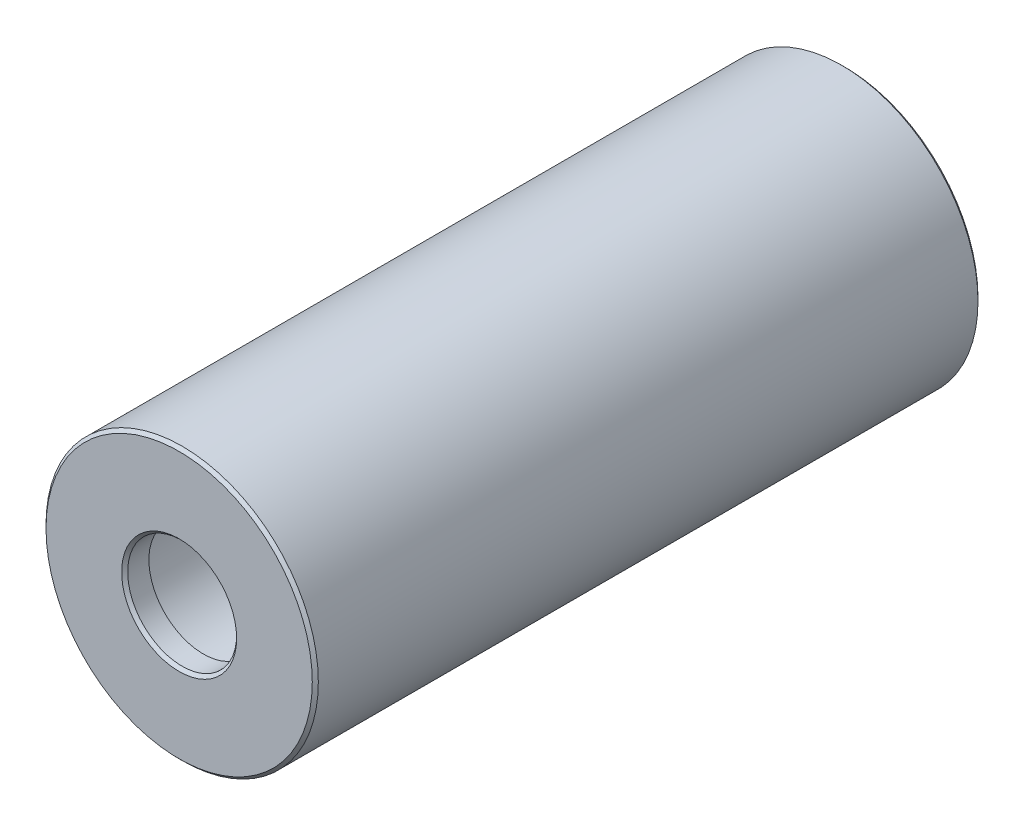
SolidWorks part; units mm, degrees
material "1060 Alloy"
ref_plane "Front Plane" through (0, 0, 0) normal (0, 0, 1) x (1, 0, 0)
ref_plane "Top Plane" through (0, 0, 0) normal (0, 1, 0) x (1, 0, 0)
ref_plane "Right Plane" through (0, 0, 0) normal (1, 0, 0) x (0, 0, -1)
sketch "Sketch1" plane through (0, 0, 0) normal (1, 0, 0) x (0, 0, -1)
  line L0 (0, 0) -> (110, 0) construction
  line L1 (0, 9.5) -> (0, 22.5)
  line L2 (0, 22.5) -> (110, 22.5)
  line L3 (110, 22.5) -> (110, 17.5)
  line L4 (109.5, 17) -> (64, 17)
  line L5 (64, 17) -> (64, 12.5)
  line L6 (63.5, 12) -> (4, 12)
  line L7 (4, 12) -> (4, 9)
  line L8 (4, 9) -> (0.5, 9)
  line L9 (110, 17.5) -> (109.5, 17)
  line L10 (64, 12.5) -> (63.5, 12)
  line L11 (0.5, 9) -> (0, 9.5)
  point P3 (0, 9)
  point P6 (110, 17)
  point P8 (64, 12)
  dimension "D1" = 110
  dimension "D2" = 45
  dimension "D3" = 34
  dimension "D4" = 24
  dimension "D5" = 18
  dimension "D6" = 4
  dimension "D7" = 60
  dimension "D8" = 46
  dimension "D9" = 0.5
  dimension "D10" = 45
  dimension "D11" = 0.5
  dimension "D12" = 45
  dimension "D13" = 0.5
  dimension "D14" = 45
revolve "Revolve1" add sketch "Sketch1" angle 360 about L0
chamfer "Chamfer1" distance 0.5 angle 45 2 edges at (22.5, 0, 0) (22.5, 0, -110)
